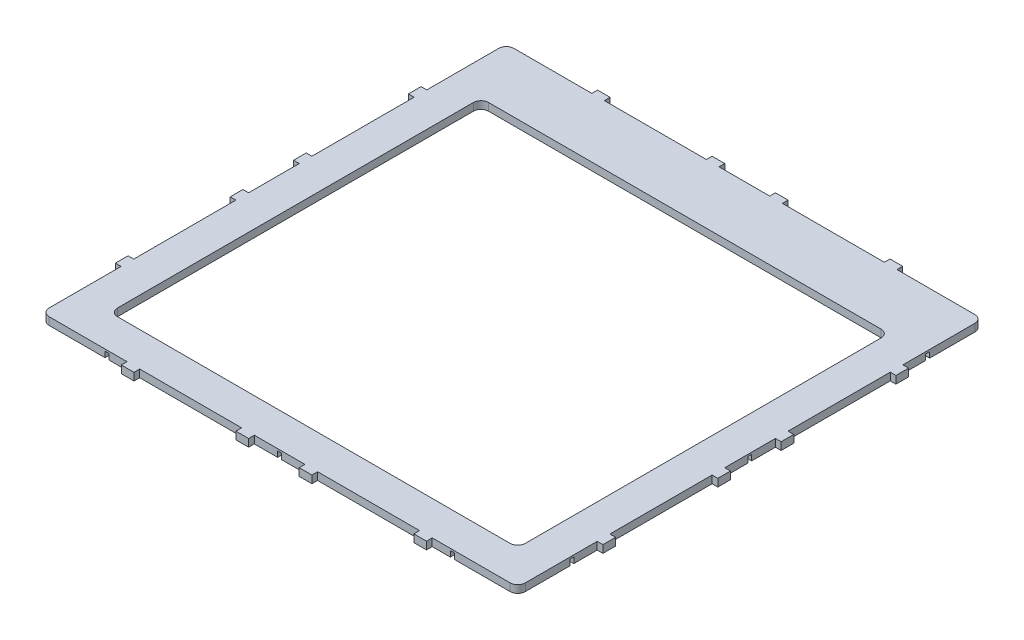
SolidWorks part; units mm, degrees
ref_plane "Alzado" through (0, 0, 0) normal (0, 0, 1) x (1, 0, 0)
ref_plane "Planta" through (0, 0, 0) normal (0, 1, 0) x (1, 0, 0)
ref_plane "Vista lateral" through (0, 0, 0) normal (1, 0, 0) x (0, 0, -1)
sketch "Croquis1" plane through (0, 0, 0) normal (0, 1, 0) x (1, 0, 0)
  line L0 (370, 0) -> (308.5, 0)
  line L1 (308.5, 0) -> (308.5, -4.5)
  line L2 (308.5, -4.5) -> (298.5, -4.5)
  line L3 (298.5, -4.5) -> (298.5, 0)
  line L4 (298.5, 0) -> (218, 0)
  line L5 (0, 6) -> (0, 62.8)
  line L6 (0, 62.8) -> (-4.5, 62.8)
  line L7 (-4.5, 62.8) -> (-4.5, 72.8)
  line L8 (-4.5, 72.8) -> (0, 72.8)
  line L9 (0, 72.8) -> (0, 153.5)
  line L10 (0, 153.5) -> (-4.5, 153.5)
  line L11 (-4.5, 153.5) -> (-4.5, 163.5)
  line L12 (-4.5, 163.5) -> (0, 163.5)
  line L13 (0, 163.5) -> (0, 203.5)
  line L14 (0, 183.5) -> (180.5, 183.5) construction
  line L15 (188, 367) -> (188, 0) construction
  line L16 (-4.5, 203.5) -> (0, 203.5)
  line L17 (-4.5, 213.5) -> (-4.5, 203.5)
  line L18 (0, 213.5) -> (-4.5, 213.5)
  line L19 (0, 294.2) -> (0, 213.5)
  line L20 (-4.5, 294.2) -> (0, 294.2)
  line L21 (-4.5, 304.2) -> (-4.5, 294.2)
  line L22 (0, 304.2) -> (-4.5, 304.2)
  line L23 (0, 361) -> (0, 304.2)
  line L24 (6, 367) -> (67.5, 367)
  line L25 (67.5, 367) -> (67.5, 371.5)
  line L26 (67.5, 371.5) -> (77.5, 371.5)
  line L27 (77.5, 371.5) -> (77.5, 367)
  line L28 (77.5, 367) -> (158, 367)
  line L29 (158, 367) -> (158, 371.5)
  line L30 (158, 371.5) -> (168, 371.5)
  line L31 (168, 371.5) -> (168, 367)
  line L32 (168, 367) -> (208, 367)
  line L33 (376, 163.5) -> (376, 203.5)
  line L34 (380.5, 163.5) -> (376, 163.5)
  line L35 (380.5, 153.5) -> (380.5, 163.5)
  line L36 (376, 153.5) -> (380.5, 153.5)
  line L37 (376, 72.8) -> (376, 153.5)
  line L38 (380.5, 72.8) -> (376, 72.8)
  line L39 (380.5, 62.8) -> (380.5, 72.8)
  line L40 (376, 62.8) -> (380.5, 62.8)
  line L41 (376, 6) -> (376, 62.8)
  line L42 (218, 0) -> (218, -4.5)
  line L43 (218, -4.5) -> (208, -4.5)
  line L44 (208, -4.5) -> (208, 0)
  line L45 (168, 0) -> (208, 0)
  line L46 (208, 371.5) -> (208, 367)
  line L47 (218, 371.5) -> (208, 371.5)
  line L48 (218, 367) -> (218, 371.5)
  line L49 (298.5, 367) -> (218, 367)
  line L50 (298.5, 371.5) -> (298.5, 367)
  line L51 (308.5, 371.5) -> (298.5, 371.5)
  line L52 (308.5, 367) -> (308.5, 371.5)
  line L53 (370, 367) -> (308.5, 367)
  line L54 (376, 361) -> (376, 304.2)
  line L55 (376, 304.2) -> (380.5, 304.2)
  line L56 (380.5, 304.2) -> (380.5, 294.2)
  line L57 (380.5, 294.2) -> (376, 294.2)
  line L58 (376, 294.2) -> (376, 213.5)
  line L59 (376, 213.5) -> (380.5, 213.5)
  line L60 (380.5, 213.5) -> (380.5, 203.5)
  line L61 (380.5, 203.5) -> (376, 203.5)
  line L62 (168, -4.5) -> (168, 0)
  line L63 (158, -4.5) -> (168, -4.5)
  line L64 (158, 0) -> (158, -4.5)
  line L65 (77.5, 0) -> (158, 0)
  line L66 (77.5, -4.5) -> (77.5, 0)
  line L67 (67.5, -4.5) -> (77.5, -4.5)
  line L68 (67.5, 0) -> (67.5, -4.5)
  line L69 (6, 0) -> (67.5, 0)
  line L71 (349, 313.9794) -> (349, 33)
  line L72 (343, 27) -> (33, 27)
  line L73 (27, 33) -> (27, 313.9581)
  line L74 (33.0419, 320) -> (342.9794, 320)
  arc A0 (33.0419, 320) -> (27, 313.9581) centre (33.0419, 313.9581) ccw
  arc A1 (27, 33) -> (33, 27) centre (33, 33) ccw
  arc A2 (343, 27) -> (349, 33) centre (343, 33) ccw
  arc A3 (349, 313.9794) -> (342.9794, 320) centre (342.9794, 313.9794) ccw
  arc A4 (0, 6) -> (6, 0) centre (6, 6) ccw
  arc A5 (370, 0) -> (376, 6) centre (370, 6) ccw
  arc A6 (376, 361) -> (370, 367) centre (370, 361) ccw
  arc A7 (6, 367) -> (0, 361) centre (6, 361) ccw
  circle A8 centre (283, 346) radius 6 construction
  circle A9 centre (283, 346) radius 6
  circle A10 centre (93, 346) radius 6 construction
  circle A11 centre (93, 346) radius 6
  dimension "D18" = 12
  dimension "D19" = 12
  dimension "D21" = 12
  dimension "D22" = 12
  dimension "D23" = 12
  dimension "D24" = 12
  dimension "D2" = 27
  dimension "D3" = 27
  dimension "D5" = 62.8
  dimension "D6" = 4.5
  dimension "D7" = 10
  dimension "D8" = 20
  dimension "D9" = 10
  dimension "D10" = 20
  dimension "D11" = 67.5
  dimension "D12" = 10
  dimension "D13" = 4.5
  dimension "D15" = 10
  dimension "D16" = 27
extrude "Saliente-Extruir1" add sketch "Croquis1" against normal blind 6
sketch "Croquis3" plane through (0, -6, 0) normal (0, -1, 0) x (1, 0, 0)
  line L0 (67.5, -367) -> (6, -367) construction
  line L1 (322.9899, 0) -> (324.5165, 0) construction
  line L2 (324.3519, -27.8842) -> (324.3519, -14.1425) construction
  line L3 (322.8019, 0) -> (325.9019, 0)
  line L4 (325.9019, -6.5002) -> (325.9019, 0)
  line L5 (327.1922, -8.0283) -> (327.1922, -9.5783)
  line L6 (322.2171, -10.8781) -> (322.3864, -10.8781)
  line L7 (321.5115, -8.0283) -> (321.5115, -9.5783)
  line L8 (324.3519, -14.1425) -> (324.3519, 7.2816) construction
  line L9 (322.8019, -6.5002) -> (322.8019, 0)
  line L10 (51.65, -367) -> (51.65, -354.5003) construction
  line L11 (53.7848, -356.1219) -> (53.6155, -356.1219)
  line L12 (326.4866, -10.8781) -> (326.3174, -10.8781)
  line L13 (186.638, -367) -> (188.1646, -367) construction
  line L14 (324.3519, -352.8575) -> (324.3519, -374.2816) construction
  line L15 (322.9899, -367) -> (324.5165, -367) construction
  line L16 (190.1348, -356.1219) -> (189.9655, -356.1219)
  line L17 (186.45, -360.4998) -> (186.45, -367)
  line L18 (185.1597, -358.9717) -> (185.1597, -357.4217)
  line L19 (185.8652, -356.1219) -> (186.0345, -356.1219)
  line L20 (188, -183.5) -> (188, -415.2196) construction
  line L21 (190.8403, -358.9717) -> (190.8403, -357.4217)
  line L22 (0, -58.0146) -> (0, -56.488) construction
  line L23 (12.8842, -42.85) -> (-0.8575, -42.85) construction
  line L24 (6.5002, -44.4) -> (0, -44.4)
  line L25 (10.8781, -40.7152) -> (10.8781, -40.8845)
  line L26 (8.0283, -45.6903) -> (9.5783, -45.6903)
  line L27 (0, -44.4) -> (0, -41.3)
  line L28 (8.0283, -40.0097) -> (9.5783, -40.0097)
  line L29 (6.5002, -41.3) -> (0, -41.3)
  line L30 (10.8781, -44.9848) -> (10.8781, -44.8155)
  line L31 (188, -183.5) -> (188, 89.0503) construction
  line L32 (363.1158, -323.7) -> (376.8575, -323.7) construction
  line L33 (0, -183.5) -> (376, -183.5) construction
  line L36 (10.8781, -185.5348) -> (10.8781, -185.3655)
  line L37 (10.8781, -181.2652) -> (10.8781, -181.4345)
  line L38 (6.5002, -184.95) -> (0, -184.95)
  line L39 (6.5002, -181.85) -> (0, -181.85)
  line L40 (8.0283, -186.2403) -> (9.5783, -186.2403)
  line L41 (0, -181.85) -> (0, -184.95)
  line L42 (8.0283, -180.5597) -> (9.5783, -180.5597)
  line L43 (0, -175.2367) -> (0, -176.7633) construction
  line L44 (12.8842, -183.4) -> (-0.8575, -183.4) construction
  line L45 (376, -58.6694) -> (376, -57.1428) construction
  line L46 (10.8781, -321.7501) -> (10.8781, -321.9194)
  line L47 (6.5002, -325.4349) -> (0, -325.4349)
  line L48 (12.8842, -323.8849) -> (-0.8575, -323.8849) construction
  line L49 (8.0283, -326.7252) -> (9.5783, -326.7252)
  line L50 (0, -322.3349) -> (0, -325.4349)
  line L51 (8.0283, -321.0445) -> (9.5783, -321.0445)
  line L52 (10.8781, -326.0196) -> (10.8781, -325.8504)
  line L53 (6.5002, -322.3349) -> (0, -322.3349)
  line L54 (0, -308.9854) -> (0, -310.512) construction
  line L55 (186.638, 0) -> (188.1646, 0) construction
  line L56 (369.4998, -322.15) -> (376, -322.15)
  line L57 (365.1219, -325.8348) -> (365.1219, -325.6655)
  line L58 (367.9717, -320.8597) -> (366.4217, -320.8597)
  line L59 (376, -322.15) -> (376, -325.25)
  line L60 (367.9717, -326.5403) -> (366.4217, -326.5403)
  line L61 (369.4998, -325.25) -> (376, -325.25)
  line L62 (365.1219, -321.5652) -> (365.1219, -321.7345)
  line L63 (363.1158, -183.5) -> (376.8575, -183.5) construction
  line L64 (376, -175.2367) -> (376, -176.7633) construction
  line L65 (367.9717, -180.3739) -> (366.4217, -180.3739)
  line L66 (376, -181.6642) -> (376, -184.7642)
  line L67 (367.9717, -186.0545) -> (366.4217, -186.0545)
  line L68 (369.4998, -181.6642) -> (376, -181.6642)
  line L69 (369.4998, -184.7642) -> (376, -184.7642)
  line L70 (365.1219, -181.0794) -> (365.1219, -181.2487)
  line L71 (365.1219, -185.349) -> (365.1219, -185.1797)
  line L72 (376, -308.3306) -> (376, -309.8572) construction
  line L73 (370, -367) -> (308.5, -367) construction
  line L74 (363.1158, -42.85) -> (376.8575, -42.85) construction
  line L75 (365.1219, -44.8627) -> (365.1219, -44.6935)
  line L76 (369.4998, -41.178) -> (376, -41.178)
  line L77 (367.9717, -39.8876) -> (366.4217, -39.8876)
  line L78 (376, -44.278) -> (376, -41.178)
  line L79 (367.9717, -45.5683) -> (366.4217, -45.5683)
  line L80 (365.1219, -40.5932) -> (365.1219, -40.7625)
  line L81 (369.4998, -44.278) -> (376, -44.278)
  line L82 (51.65, -27.8842) -> (51.65, -14.1425) construction
  line L83 (50.8848, 0) -> (52.4114, 0) construction
  line L84 (50.1, 0) -> (53.2, 0)
  line L85 (53.2, -6.5002) -> (53.2, 0)
  line L86 (324.3519, -339.1158) -> (324.3519, -352.8575) construction
  line L87 (189.55, -360.4998) -> (189.55, -367)
  line L88 (186.45, -367) -> (189.55, -367)
  line L89 (326.4866, -356.1219) -> (326.3174, -356.1219)
  line L90 (322.8019, -360.4998) -> (322.8019, -367)
  line L91 (321.5115, -358.9717) -> (321.5115, -357.4217)
  line L92 (322.2171, -356.1219) -> (322.3864, -356.1219)
  line L93 (327.1922, -358.9717) -> (327.1922, -357.4217)
  line L94 (325.9019, -360.4998) -> (325.9019, -367)
  line L95 (50.8848, -367) -> (52.4114, -367) construction
  line L96 (51.65, -339.1158) -> (51.65, -352.8575) construction
  line L97 (50.1, -360.4998) -> (50.1, -367)
  line L98 (48.8097, -358.9717) -> (48.8097, -357.4217)
  line L99 (49.5152, -356.1219) -> (49.6845, -356.1219)
  line L100 (54.4903, -358.9717) -> (54.4903, -357.4217)
  line L101 (53.2, -360.4998) -> (53.2, -367)
  line L102 (50.1, -367) -> (53.2, -367)
  line L103 (186.45, 0) -> (189.55, 0)
  line L104 (189.55, -6.5002) -> (189.55, 0)
  line L105 (190.8403, -8.0283) -> (190.8403, -9.5783)
  line L106 (185.8652, -10.8781) -> (186.0345, -10.8781)
  line L107 (185.1597, -8.0283) -> (185.1597, -9.5783)
  line L108 (186.45, -6.5002) -> (186.45, 0)
  line L109 (190.1348, -10.8781) -> (189.9655, -10.8781)
  line L110 (322.8019, -367) -> (325.9019, -367)
  line L112 (0, -62.8) -> (0, -6) construction
  line L113 (54.4903, -8.0283) -> (54.4903, -9.5783)
  line L114 (49.5152, -10.8781) -> (49.6845, -10.8781)
  line L115 (48.8097, -8.0283) -> (48.8097, -9.5783)
  line L116 (50.1, -6.5002) -> (50.1, 0)
  line L117 (53.7848, -10.8781) -> (53.6155, -10.8781)
  line L120 (6, 0) -> (67.5, 0) construction
  arc A0 (327.1922, -8.0283) -> (325.9019, -6.5002) centre (325.6422, -8.0283) ccw
  arc A1 (322.2171, -10.8781) -> (321.5115, -9.5783) centre (323.0615, -9.5783) cw
  arc A2 (321.5115, -8.0283) -> (322.8019, -6.5002) centre (323.0615, -8.0283) cw
  arc A3 (326.4866, -10.8781) -> (327.1922, -9.5783) centre (325.6422, -9.5783) ccw
  arc A4 (326.3174, -10.8781) -> (322.3864, -10.8781) centre (324.3519, -10.1476) cw
  arc A5 (189.9655, -356.1219) -> (186.0345, -356.1219) centre (188, -356.8524) ccw
  arc A6 (190.1348, -356.1219) -> (190.8403, -357.4217) centre (189.2903, -357.4217) cw
  arc A7 (185.1597, -358.9717) -> (186.45, -360.4998) centre (186.7097, -358.9717) ccw
  arc A8 (185.8652, -356.1219) -> (185.1597, -357.4217) centre (186.7097, -357.4217) ccw
  arc A9 (190.8403, -358.9717) -> (189.55, -360.4998) centre (189.2903, -358.9717) cw
  arc A10 (8.0283, -45.6903) -> (6.5002, -44.4) centre (8.0283, -44.1403) cw
  arc A11 (10.8781, -40.8845) -> (10.8781, -44.8155) centre (10.1476, -42.85) cw
  arc A12 (10.8781, -40.7152) -> (9.5783, -40.0097) centre (9.5783, -41.5597) ccw
  arc A13 (10.8781, -44.9848) -> (9.5783, -45.6903) centre (9.5783, -44.1403) cw
  arc A14 (8.0283, -40.0097) -> (6.5002, -41.3) centre (8.0283, -41.5597) ccw
  arc A15 (8.0283, -180.5597) -> (6.5002, -181.85) centre (8.0283, -182.1097) ccw
  arc A16 (10.8781, -185.5348) -> (9.5783, -186.2403) centre (9.5783, -184.6903) cw
  arc A17 (10.8781, -185.3655) -> (10.8781, -181.4345) centre (10.1476, -183.4) ccw
  arc A18 (10.8781, -181.2652) -> (9.5783, -180.5597) centre (9.5783, -182.1097) ccw
  arc A19 (8.0283, -186.2403) -> (6.5002, -184.95) centre (8.0283, -184.6903) cw
  arc A20 (8.0283, -326.7252) -> (6.5002, -325.4349) centre (8.0283, -325.1752) cw
  arc A21 (10.8781, -321.7501) -> (9.5783, -321.0445) centre (9.5783, -322.5945) ccw
  arc A22 (10.8781, -326.0196) -> (9.5783, -326.7252) centre (9.5783, -325.1752) cw
  arc A23 (10.8781, -325.8504) -> (10.8781, -321.9194) centre (10.1476, -323.8849) ccw
  arc A24 (8.0283, -321.0445) -> (6.5002, -322.3349) centre (8.0283, -322.5945) ccw
  arc A25 (367.9717, -320.8597) -> (369.4998, -322.15) centre (367.9717, -322.4097) cw
  arc A26 (365.1219, -325.6655) -> (365.1219, -321.7345) centre (365.8524, -323.7) cw
  arc A27 (365.1219, -325.8348) -> (366.4217, -326.5403) centre (366.4217, -324.9903) ccw
  arc A28 (365.1219, -321.5652) -> (366.4217, -320.8597) centre (366.4217, -322.4097) cw
  arc A29 (367.9717, -326.5403) -> (369.4998, -325.25) centre (367.9717, -324.9903) ccw
  arc A30 (367.9717, -186.0545) -> (369.4998, -184.7642) centre (367.9717, -184.5045) ccw
  arc A31 (365.1219, -181.0794) -> (366.4217, -180.3739) centre (366.4217, -181.9239) cw
  arc A32 (365.1219, -185.1797) -> (365.1219, -181.2487) centre (365.8524, -183.2142) cw
  arc A33 (365.1219, -185.349) -> (366.4217, -186.0545) centre (366.4217, -184.5045) ccw
  arc A34 (367.9717, -180.3739) -> (369.4998, -181.6642) centre (367.9717, -181.9239) cw
  arc A35 (367.9717, -39.8876) -> (369.4998, -41.178) centre (367.9717, -41.4376) cw
  arc A36 (365.1219, -44.8627) -> (366.4217, -45.5683) centre (366.4217, -44.0183) ccw
  arc A37 (365.1219, -40.5932) -> (366.4217, -39.8876) centre (366.4217, -41.4376) cw
  arc A38 (365.1219, -40.7625) -> (365.1219, -44.6935) centre (365.8524, -42.728) ccw
  arc A39 (367.9717, -45.5683) -> (369.4998, -44.278) centre (367.9717, -44.0183) ccw
  arc A40 (326.3174, -356.1219) -> (322.3864, -356.1219) centre (324.3519, -356.8524) ccw
  arc A41 (326.4866, -356.1219) -> (327.1922, -357.4217) centre (325.6422, -357.4217) cw
  arc A42 (321.5115, -358.9717) -> (322.8019, -360.4998) centre (323.0615, -358.9717) ccw
  arc A43 (322.2171, -356.1219) -> (321.5115, -357.4217) centre (323.0615, -357.4217) ccw
  arc A44 (327.1922, -358.9717) -> (325.9019, -360.4998) centre (325.6422, -358.9717) cw
  arc A45 (53.6155, -356.1219) -> (49.6845, -356.1219) centre (51.65, -356.8524) ccw
  arc A46 (53.7848, -356.1219) -> (54.4903, -357.4217) centre (52.9403, -357.4217) cw
  arc A47 (48.8097, -358.9717) -> (50.1, -360.4998) centre (50.3597, -358.9717) ccw
  arc A48 (49.5152, -356.1219) -> (48.8097, -357.4217) centre (50.3597, -357.4217) ccw
  arc A49 (54.4903, -358.9717) -> (53.2, -360.4998) centre (52.9403, -358.9717) cw
  arc A50 (190.8403, -8.0283) -> (189.55, -6.5002) centre (189.2903, -8.0283) ccw
  arc A51 (185.8652, -10.8781) -> (185.1597, -9.5783) centre (186.7097, -9.5783) cw
  arc A52 (185.1597, -8.0283) -> (186.45, -6.5002) centre (186.7097, -8.0283) cw
  arc A53 (190.1348, -10.8781) -> (190.8403, -9.5783) centre (189.2903, -9.5783) ccw
  arc A54 (189.9655, -10.8781) -> (186.0345, -10.8781) centre (188, -10.1476) cw
  arc A55 (54.4903, -8.0283) -> (53.2, -6.5002) centre (52.9403, -8.0283) ccw
  arc A56 (49.5152, -10.8781) -> (48.8097, -9.5783) centre (50.3597, -9.5783) cw
  arc A57 (48.8097, -8.0283) -> (50.1, -6.5002) centre (50.3597, -8.0283) cw
  arc A58 (53.7848, -10.8781) -> (54.4903, -9.5783) centre (52.9403, -9.5783) ccw
  arc A59 (53.6155, -10.8781) -> (49.6845, -10.8781) centre (51.65, -10.1476) cw
  point P22 (324.3519, 0)
  point P75 (0, -42.85)
  point P112 (0, -176)
  point P141 (0, -323.8849)
  point P147 (376, -323.7)
  point P169 (376, -176)
  point P208 (51.65, 0)
  point P209 (376, -42.728)
  point P258 (51.65, -367)
  point P271 (188, 0)
  point P273 (188, -367)
  point P274 (324.3519, -367)
  dimension "D3" = 3.1
  dimension "D4" = 3.1
  dimension "D7" = 43.1151
  dimension "D9" = 140.2
  dimension "D1" = 3.1
  dimension "D2" = 3.1
  dimension "D5" = 51.65
  dimension "D6" = 42.85
  dimension "D8" = 43.3
  dimension "D10" = 140.65
extrude "Cortar-Extruir1" cut sketch "Croquis3" against normal blind 4.5
sketch "Croquis4" plane through (0, 0, 0) normal (0, 1, 0) x (1, 0, 0)
  line L1 (82.6181, 354.589) -> (102.3078, 354.589)
  line L2 (82.6181, 354.589) -> (82.6181, 336.6496)
  line L3 (82.6181, 336.6496) -> (102.3078, 336.6496)
  line L4 (102.3078, 354.589) -> (102.3078, 336.6496)
  line L5 (272.3409, 354.589) -> (291.7854, 354.589)
  line L6 (272.3409, 354.589) -> (272.3409, 336.6496)
  line L7 (272.3409, 336.6496) -> (291.7854, 336.6496)
  line L8 (291.7854, 354.589) -> (291.7854, 336.6496)
extrude "Saliente-Extruir2" add sketch "Croquis4" against normal blind 1.5
equation "\"Ancho_panel\"= 385'Ancho del panel"
equation "\"Alto_panel\"= 420'Alto del panel izquierdo"
equation "\"Altura_base_taladros\"= 70'Alto taladros de la base eje Z"
equation "\"Altura_superior_taladros\"= 8mm'Distancia taladros a top"
equation "\"Distancia_vert_entre_horizontales_ensambles\"= \"Alto_panel\" - \"Altura_base_taladros\" - \"Altura_superior_taladros\"'Distancia vertical entre horizontales de ensambles"
equation "\"Latrales_separacion_barras_a_escalon_bajo\"= 12.5'Separación entre las barras y el escalón inferior de la parte superior"
equation "\"Espacio_tensor_correa_motor\"= 8.5mm'Espacio para mover el motor en vertical y tensar la correa"
equation "\"Ancho_panel_interior\"= \"Ancho_panel\" - 9mm'Ancho panel interior"
equation "\"Fondo_panel_interior\"= \"Ancho_panel\" - 9mm'Fondo panel interior"
